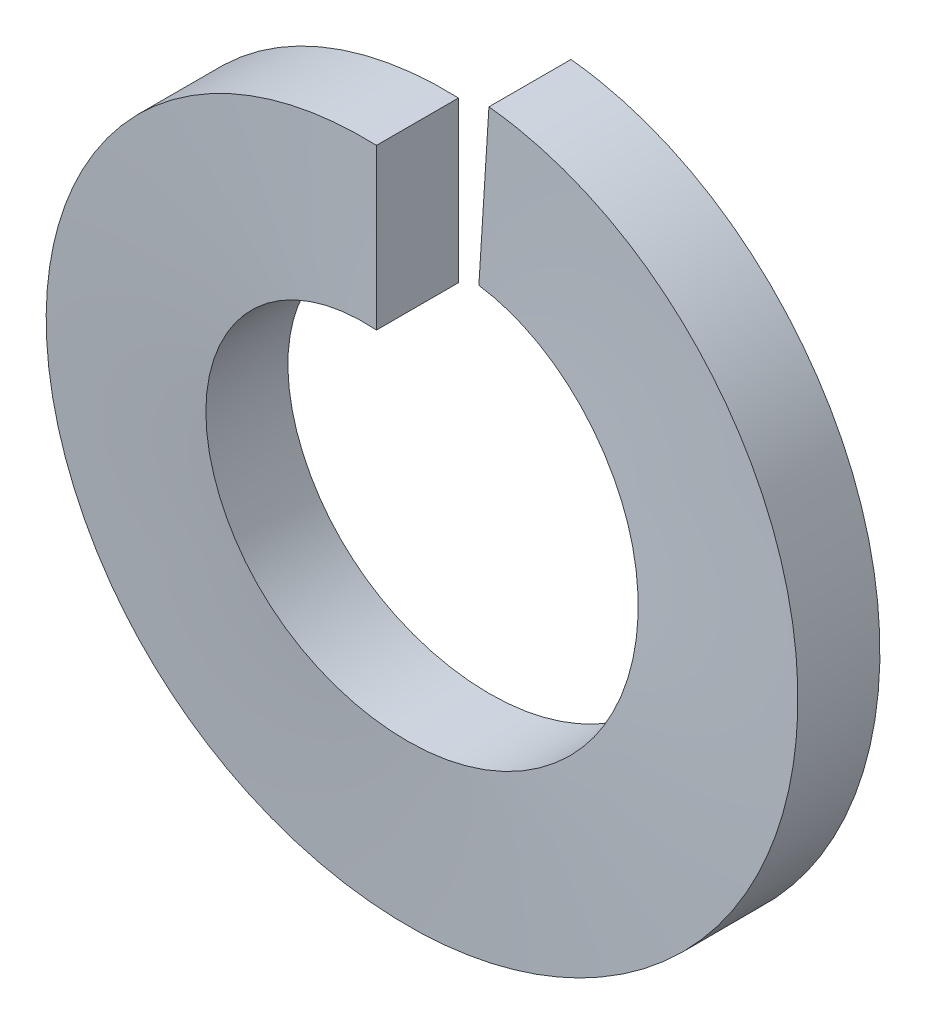
SolidWorks part; units mm, degrees
material "AISI 304"
ref_plane "Front Plane" through (0, 0, 0) normal (0, 0, 1) x (1, 0, 0)
ref_plane "Top Plane" through (0, 0, 0) normal (0, 1, 0) x (1, 0, 0)
ref_plane "Right Plane" through (0, 0, 0) normal (1, 0, 0) x (0, 0, -1)
sketch "Sketch1" plane through (0, 0, 0) normal (0, 0, 1) x (1, 0, 0)
  line L0 (0, 2.1844) -> (0, 1.1938) construction
  circle A0 centre (0, 0) radius 2.1844
  circle A1 centre (0, 0) radius 1.1938 construction
  dimension "ID" = 2.3876
  dimension "OD" = 4.3688
curve "Helix/Spiral1" pitch 0.5644 height 0.5588 turns 0.99 parameters "HT"=0.5588
sketch "Sketch2" plane through (0, 0, 0) normal (1, 0, 0) x (0, 0, -1)
  line L1 (0, 2.1844) -> (-0.508, 2.1844)
  line L2 (0, 2.1844) -> (0, 1.1938)
  line L3 (0, 1.1938) -> (-0.508, 1.1938)
  line L4 (-0.508, 2.1844) -> (-0.508, 1.1938)
  dimension "THK" = 0.508
sweep "Sweep1" add profiles "Sketch2" path "Helix/Spiral1"
equation "\"HT@Helix/Spiral1\" = \"THK@Sketch2\"*1.1"
